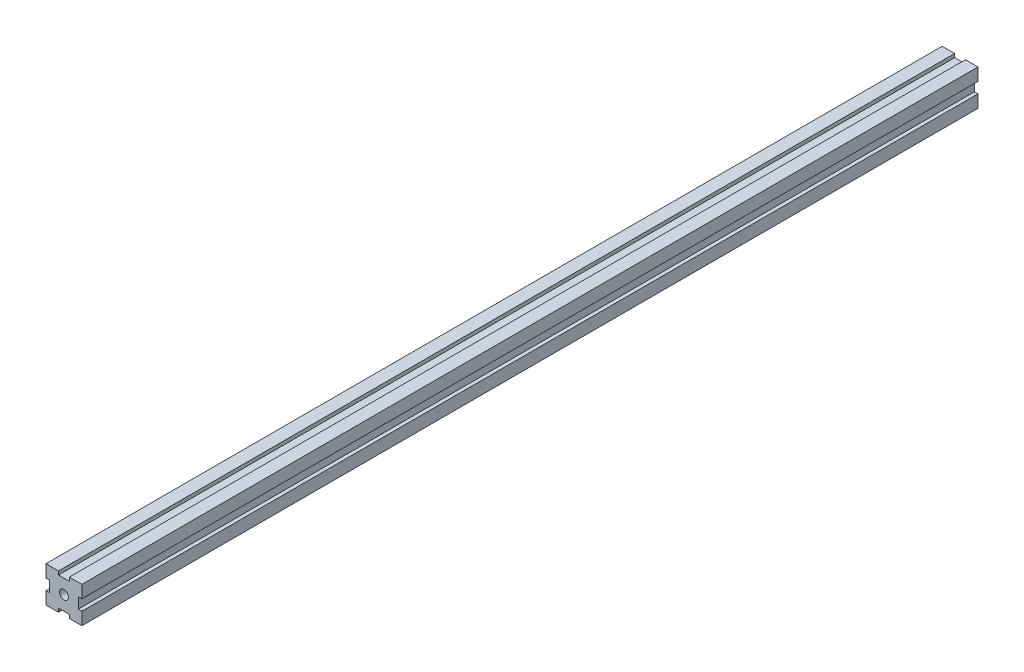
SolidWorks part; units mm, degrees
ref_plane "前视基准面" through (0, 0, 0) normal (0, 0, 1) x (1, 0, 0)
ref_plane "上视基准面" through (0, 0, 0) normal (0, 1, 0) x (1, 0, 0)
ref_plane "右视基准面" through (0, 0, 0) normal (1, 0, 0) x (0, 0, -1)
sketch "草图1" plane through (0, 0, 0) normal (0, 0, 1) x (1, 0, 0)
  line L0 (0, -13) -> (0, -20)
  line L1 (0, 0) -> (7, 0)
  line L2 (0, 0) -> (0, -7)
  line L3 (0, -20) -> (7, -20)
  line L4 (20, 0) -> (20, -7)
  line L5 (20, -7) -> (18, -7)
  line L6 (13, -20) -> (20, -20)
  line L7 (20, -13) -> (18, -13)
  line L8 (18, -7) -> (18, -13)
  line L9 (0, -7) -> (2, -7)
  line L10 (13, 0) -> (20, 0)
  line L11 (0, -13) -> (2, -13)
  line L12 (2, -7) -> (2, -13)
  line L13 (20, -13) -> (20, -20)
  line L14 (7, 0) -> (7, -2)
  line L15 (7, -2) -> (13, -2)
  line L16 (13, 0) -> (13, -2)
  line L17 (0, -7) -> (0, -13) construction
  line L18 (7, -20) -> (7, -18)
  line L19 (7, -18) -> (13, -18)
  line L20 (13, -20) -> (13, -18)
  line L21 (7, 0) -> (13, 0) construction
  line L22 (20, -7) -> (20, -13) construction
  line L23 (13, -20) -> (7, -20) construction
  line L24 (2, -10) -> (18, -10) construction
  line L25 (10, -2) -> (10, -18) construction
  circle A0 centre (10, -10) radius 2.5
  point P21 (10, 0)
  point P22 (10, -2)
  point P23 (10, -18)
  point P24 (2, -10)
  point P25 (18, -10)
  point P26 (0, -10)
  point P33 (0, 0)
  dimension "D13" = 5
  dimension "D1" = 20
  dimension "D2" = 20
  dimension "D3" = 6
  dimension "D4" = 6
  dimension "D5" = 6
  dimension "D6" = 6
  dimension "D7" = 10
  dimension "D8" = 10
  dimension "D9" = 2
  dimension "D10" = 2
  dimension "D11" = 2
  dimension "D12" = 2
extrude "凸台-拉伸1" add sketch "草图1" along normal blind 500
